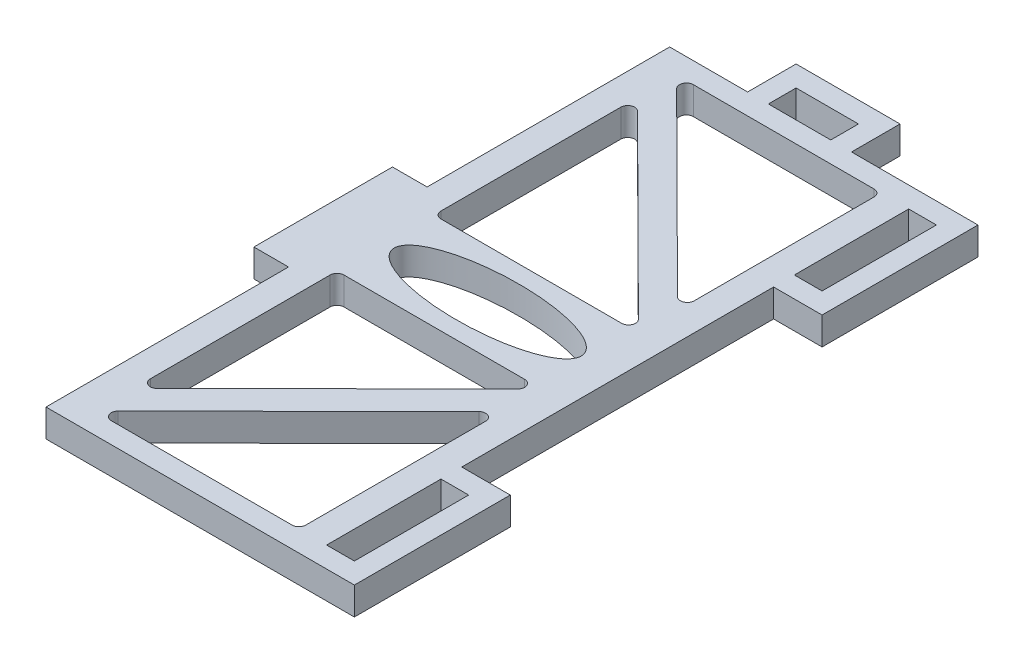
SolidWorks part; units mm, degrees
ref_plane "Front Plane" through (0, 0, 0) normal (0, 0, 1) x (1, 0, 0)
ref_plane "Top Plane" through (0, 0, 0) normal (0, 1, 0) x (1, 0, 0)
ref_plane "Right Plane" through (0, 0, 0) normal (1, 0, 0) x (0, 0, -1)
sketch "Sketch1" plane through (0, 0, 0) normal (0, 1, 0) x (1, 0, 0)
  line L0 (-18.75, 45) -> (-18.75, -45)
  line L1 (-18.75, -45) -> (18.75, -45)
  line L2 (18.75, -45) -> (18.75, 45)
  line L3 (18.75, 45) -> (-18.75, 45)
  line L4 (-14.75, 42) -> (14.75, 42)
  line L5 (18.75, 45) -> (25.75, 45)
  line L6 (18.75, 45) -> (18.75, 22.5)
  line L7 (18.75, 22.5) -> (25.75, 22.5)
  line L8 (25.75, 45) -> (25.75, 22.5)
  line L9 (18.75, -45) -> (25.75, -45)
  line L10 (18.75, -45) -> (18.75, -22.5)
  line L11 (18.75, -22.5) -> (25.75, -22.5)
  line L12 (25.75, -45) -> (25.75, -22.5)
  line L13 (18.75, 42) -> (22.75, 42)
  line L14 (18.75, 42) -> (18.75, 25.5)
  line L15 (18.75, 25.5) -> (22.75, 25.5)
  line L16 (22.75, 42) -> (22.75, 25.5)
  line L17 (18.75, -25.5) -> (22.75, -25.5)
  line L18 (18.75, -25.5) -> (18.75, -42)
  line L19 (18.75, -42) -> (22.75, -42)
  line L20 (22.75, -25.5) -> (22.75, -42)
  line L21 (-18.75, 10) -> (-23.75, 10)
  line L22 (-18.75, 10) -> (-18.75, -10)
  line L23 (-18.75, -10) -> (-23.75, -10)
  line L24 (-23.75, 10) -> (-23.75, -10)
  line L25 (14.75, 42) -> (14.75, 12.6431)
  line L26 (14.75, 12.6431) -> (-14.75, 42)
  line L27 (-14.75, 36.3569) -> (14.75, 7)
  line L28 (14.75, 7) -> (-14.75, 7)
  line L29 (-14.75, 7) -> (-14.75, 36.3569)
  line L30 (-23.75, 0) -> (18.75, 0) construction
  line L31 (14.75, -42) -> (14.75, -12.6431)
  line L32 (-14.75, -42) -> (14.75, -42)
  line L33 (14.75, -12.6431) -> (-14.75, -42)
  line L34 (14.75, -7) -> (-14.75, -7)
  line L35 (-14.75, -36.3569) -> (14.75, -7)
  line L36 (-14.75, -7) -> (-14.75, -36.3569)
  line L38 (-7.5, 45) -> (7.5, 45)
  line L39 (-7.5, 45) -> (-7.5, 52)
  line L40 (-7.5, 52) -> (7.5, 52)
  line L41 (7.5, 45) -> (7.5, 52)
  line L42 (-4.5, 45) -> (4.5, 45)
  line L43 (-4.5, 45) -> (-4.5, 49)
  line L44 (-4.5, 49) -> (4.5, 49)
  line L45 (4.5, 45) -> (4.5, 49)
  point P4 (0, 45)
  point P6 (-18.75, 0)
  point P25 (-21.25, -10)
  point P48 (0, 49)
  dimension "D1" = 90
  dimension "D2" = 37.5
  dimension "D3" = 45
  dimension "D4" = 7
  dimension "D5" = 20
  dimension "D6" = 5
  dimension "D7" = 35
  dimension "D8" = 4
  dimension "D9" = 3
  dimension "D10" = 3
  dimension "D11" = 3
  dimension "D12" = 3
  dimension "D13" = 4
  dimension "D14" = 4
  dimension "D15" = 4
  dimension "D16" = 7
  dimension "D17" = 7
  dimension "D18" = 4
  dimension "D19" = 3
  dimension "D20" = 3
  dimension "D21" = 15
extrude "Boss-Extrude1" add sketch "Sketch1" along normal blind 4 contours L2 L10 L6 L3 L0 L1 | L13 L16 L15 L2 L7 L8 L5 L6 | L17 L20 L19 L2 L9 L12 L11 L10 | L0 L30 L2 L6 L3 L28 L29 L27 L25 L26 L4 | L45 L3 L41 L40 L39 L43 L44 | L34 L36 L35 | L22 L21 L24 L23 | L31 L33 L32
fillet "Fillet1" radius 1 12 edges at (14.75, 2, 12.6431) (-14.75, 2, 36.3569) (-14.75, 2, 7) (14.75, 2, 7) (14.75, 2, 42) (-14.75, 2, 42) (-14.75, 2, -36.3569) (-14.75, 2, -42) (14.75, 2, -42) (-14.75, 2, -7) (14.75, 2, -7) (14.75, 2, -12.6431)
sketch "Sketch2" plane through (0, 4, 0) normal (0, 1, 0) x (1, 0, 0)
  ellipse E0 centre (0, 0) end of major axis (13.5, 0) minor radius 4.5
  point P1 (0, 0)
  point P7 (13.5, 0)
  dimension "D1" = 4.5
  dimension "D2" = 13.5
extrude "Cut-Extrude1" cut sketch "Sketch2" against normal through all
